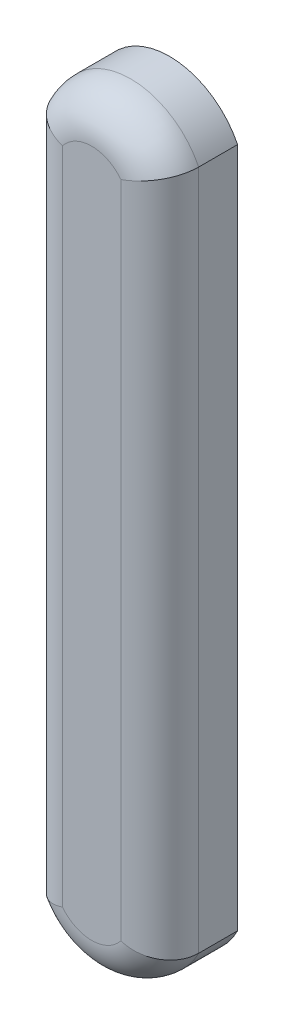
SolidWorks part; units mm, degrees
material "Plastique personnalisé"
ref_plane "Plan de face" through (0, 0, 0) normal (0, 0, 1) x (1, 0, 0)
ref_plane "Plan de dessus" through (0, 0, 0) normal (0, 1, 0) x (1, 0, 0)
ref_plane "Plan de droite" through (0, 0, 0) normal (1, 0, 0) x (0, 0, -1)
sketch "Esquisse1" plane through (0, 0, 0) normal (0, 0, 1) x (1, 0, 0)
  line L0 (0, 0.875) -> (0.35, 0.875) construction
  line L2 (0, 0) -> (0, 1.75)
  line L4 (0.35, 0) -> (0.35, 1.75)
  arc A0 (0, 1.75) -> (0.35, 1.75) centre (0.175, 1.664) cw
  arc A1 (0, 0) -> (0.35, 0) centre (0.175, 0.086) ccw
  dimension "D1" = 1.75
  dimension "D2" = 0.35
  dimension "D3" = 1.75
extrude "Boss.-Extru.1" add sketch "Esquisse1" along normal blind 0.2
fillet "Congé1" radius 0.1 4 edges at (0.175, -0.109, 0.2) (0, 0.875, 0.2) (0.35, 0.875, 0.2) (0.175, 1.859, 0.2)
